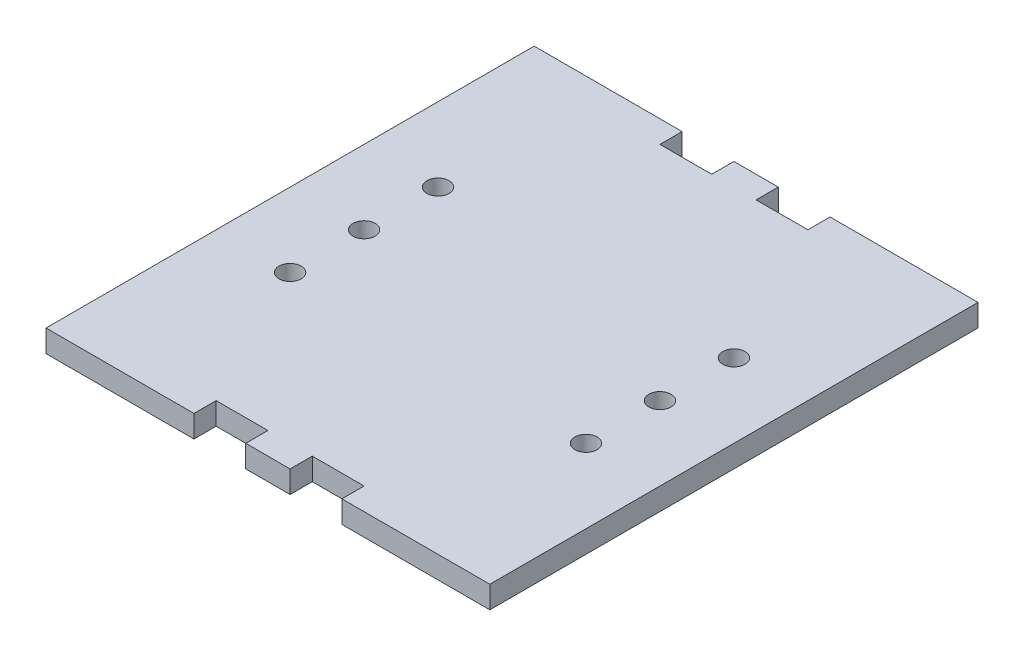
SolidWorks part; units mm, degrees
ref_plane "前视基准面" through (0, 0, 0) normal (0, 0, 1) x (1, 0, 0)
ref_plane "上视基准面" through (0, 0, 0) normal (0, 1, 0) x (1, 0, 0)
ref_plane "右视基准面" through (0, 0, 0) normal (1, 0, 0) x (0, 0, -1)
sketch "草图1" plane through (0, 0, 0) normal (0, 1, 0) x (1, 0, 0)
  line L2 (-3, 36) -> (3, 36)
  line L3 (3, 36) -> (3, 33)
  line L4 (3, 33) -> (10, 33)
  line L5 (10, 33) -> (10, 36)
  line L6 (10, 36) -> (30, 36)
  line L7 (30, 36) -> (30, -36)
  line L9 (-30, 36) -> (-30, -36)
  line L10 (-10, 36) -> (-30, 36)
  line L11 (-10, 33) -> (-10, 36)
  line L12 (-3, 33) -> (-10, 33)
  line L13 (-3, 36) -> (-3, 33)
  line L14 (10, -33) -> (10, -36)
  line L15 (10, -36) -> (30, -36)
  line L16 (3, -33) -> (10, -33)
  line L17 (3, -36) -> (3, -33)
  line L18 (-3, -36) -> (-3, -33)
  line L19 (-3, -36) -> (3, -36)
  line L20 (-10, -33) -> (-10, -36)
  line L21 (-10, -36) -> (-30, -36)
  line L22 (-3, -33) -> (-10, -33)
  circle A0 centre (-20, 0) radius 1.5
  circle A2 centre (-20, 10) radius 1.5
  circle A3 centre (-20, -10) radius 1.5
  circle A4 centre (20, -10) radius 1.5
  circle A5 centre (20, 0) radius 1.5
  circle A6 centre (20, 10) radius 1.5
  point P24 (-30, 0)
extrude "凸台-拉伸1" add sketch "草图1" along normal blind 3
sketch "草图2" plane through (0, 3, 0) normal (0, 1, 0) x (1, 0, 0)
  line L0 (30, -33) -> (10, -33)
  line L1 (30, -36) -> (30, 36) construction
  line L2 (10, -33) -> (10, -30)
  line L3 (10, -30) -> (3, -30)
  line L4 (3, -30) -> (3, -33)
  line L5 (3, -33) -> (-3, -33)
  line L6 (-3, -33) -> (-3, -30)
  line L7 (-3, -30) -> (-10, -30)
  line L8 (-10, -30) -> (-10, -33)
  line L9 (-10, -33) -> (-30, -33)
  line L10 (-30, 36) -> (-30, -36) construction
  line L11 (20, 0) -> (-20, 0)
  line L12 (-10, 30) -> (-10, 33)
  line L13 (-10, 33) -> (-30, 33)
  line L14 (-3, 33) -> (-3, 30)
  line L15 (-3, 30) -> (-10, 30)
  line L16 (3, 33) -> (-3, 33)
  line L17 (3, 30) -> (3, 33)
  line L18 (10, 30) -> (3, 30)
  line L19 (10, 33) -> (10, 30)
  line L20 (30, 33) -> (10, 33)
  line L21 (30, -33) -> (30, -51.1453)
  line L22 (30, -51.1453) -> (-30, -51.1453)
  line L23 (-30, -51.1453) -> (-30, -33)
  line L24 (-30, 33) -> (-30, 45.2589)
  line L25 (-30, 45.2589) -> (30, 45.2589)
  line L26 (30, 45.2589) -> (30, 33)
  line M14 (3, 33) -> (3, 36)
  line M15 (3, 36) -> (-3, 36)
  line M16 (-3, 36) -> (-3, 33)
  line M17 (-3, 33) -> (-10, 33)
  line M18 (-10, 33) -> (-10, 36)
  line M19 (-10, 36) -> (-30, 36)
  line M20 (-30, 36) -> (-30, -36)
  line M21 (-30, -36) -> (-10, -36)
  line M22 (-10, -36) -> (-10, -33)
  line M23 (-10, -33) -> (-3, -33)
  line M24 (-3, -33) -> (-3, -36)
  line M25 (-3, -36) -> (3, -36)
  line M26 (3, -36) -> (3, -33)
  line M27 (3, -33) -> (10, -33)
  line M28 (10, -33) -> (10, -36)
  line M29 (10, -36) -> (30, -36)
  line M30 (30, -36) -> (30, 36)
  line M31 (30, 36) -> (10, 36)
  line M32 (10, 36) -> (10, 33)
  line M33 (10, 33) -> (3, 33)
extrude "切除-拉伸1" cut sketch "草图2" against normal blind 3 contours L23 L22 L21 M29 M28 M27 M26 M25 M24 M23 M22 M21 | L0 M30 M28 M29 | L3 L4 L2 M27 | L5 M26 M24 M25 | L7 L8 L6 M23 | L9 M22 M20 M21 | L13 M18 M19 M20 | L15 L14 L12 M17 | L16 M14 M15 M16 | L19 L17 L18 M33 | L20 M30 M31 M32
